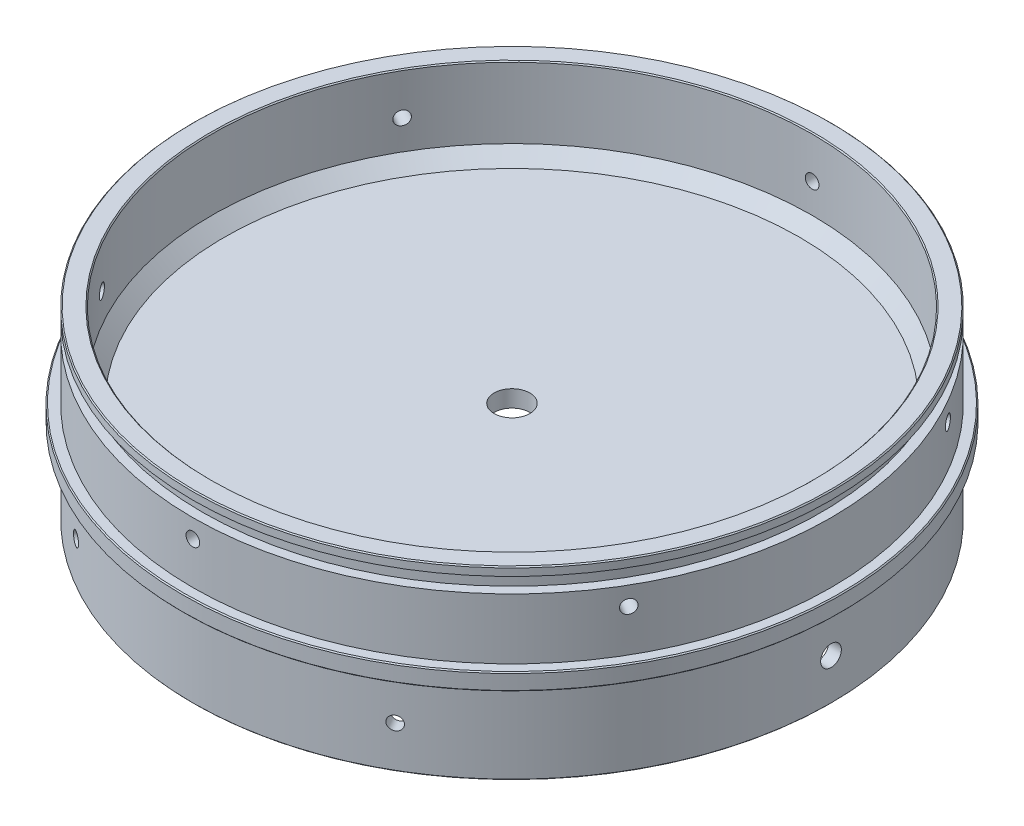
SolidWorks part; units mm, degrees
material "7075-T6 (SN)"
ref_plane "Front Plane" through (0, 0, 0) normal (0, 0, 1) x (1, 0, 0)
ref_plane "Top Plane" through (0, 0, 0) normal (0, 1, 0) x (1, 0, 0)
ref_plane "Right Plane" through (0, 0, 0) normal (1, 0, 0) x (0, 0, -1)
ref_plane "Plane1" through (0, 0, 0) normal (0, 0, -1) x (-1, 0, 0)
sketch "Sketch1" plane through (0, 0, 0) normal (0, 0, -1) x (-1, 0, 0)
  line L0 (-78.35, 0) -> (0, 0)
  line L1 (0, 0) -> (0, 24)
  line L2 (0, 24) -> (-75.89, 24)
  line L3 (-75.89, 24) -> (-75.89, 22)
  line L4 (-75.89, 22) -> (-73.64, 22)
  line L5 (-73.64, 22) -> (-73.64, 18.4)
  line L6 (-73.64, 18.4) -> (-75.89, 18.4)
  line L7 (-75.89, 18.4) -> (-75.89, 4)
  line L8 (-75.89, 4) -> (-78.35, 4)
  line L9 (-78.35, 4) -> (-78.35, 0)
  line L10 (0, 0) -> (0, 24) construction
revolve "Revolve1" add sketch "Sketch1" angle 360 about L10
sketch "Sketch2" plane through (0, 0, 0) normal (0, -1, 0) x (1, 0, 0)
  circle A0 centre (0, 0) radius 75.89
extrude "Boss-Extrude1" add sketch "Sketch2" along normal blind 20
sketch "Sketch3" plane through (0, 0, 0) normal (0, 0, 1) x (1, 0, 0)
  line L0 (71.39, 24) -> (0, 24)
  line L1 (0, 24) -> (0, -20)
  line L2 (0, -20) -> (72.89, -20)
  line L3 (72.89, -20) -> (72.89, 0)
  line L4 (72.89, 0) -> (4.25, 0)
  line L5 (4.25, 0) -> (4.25, 4)
  line L6 (4.25, 4) -> (71.39, 4)
  line L7 (71.39, 4) -> (71.39, 24)
  line L8 (0, 24) -> (0, -20) construction
revolve "Cut-Revolve1" cut sketch "Sketch3" angle 360 about L8
hole_wizard "M3 Clearance Hole1" positions "3DSketch1" profile "Sketch4" hole size "M3" standard "ANSI Metric"
sketch3d "3DSketch1"
  point P0 (65.7227, 14, -37.945)
sketch "Sketch4" plane through (65.7227, 14, -37.945) normal (0, 1, 0) x (-0.5, 0, -0.866)
  line L0 (0, 0) -> (0, 156.2984)
  line L1 (0, 156.2984) -> (1.62, 156.2984)
  line L2 (1.62, 156.2984) -> (1.62, 0)
  line L5 (1.62, 0) -> (0, 0)
  line L10 (0, 156.2984) -> (-1.62, 156.2984) construction
  line L11 (0, -6.35) -> (0, 107.95) construction
  dimension "Hole Dia." = 3.24
  dimension "Hole Depth" = 156.2984
  dimension "Drill Angle" = 180
hole_wizard "M3 Clearance Hole2" positions "3DSketch2" profile "Sketch5" hole size "M3" standard "ANSI Metric"
sketch3d "3DSketch2"
  point P0 (65.7227, 14, 37.945)
sketch "Sketch5" plane through (65.7227, 14, 37.945) normal (0, 1, 0) x (0.5, 0, -0.866)
  line L0 (0, 0) -> (0, 156.2984)
  line L1 (0, 156.2984) -> (1.62, 156.2984)
  line L2 (1.62, 156.2984) -> (1.62, 0)
  line L5 (1.62, 0) -> (0, 0)
  line L10 (0, 156.2984) -> (-1.62, 156.2984) construction
  line L11 (0, -6.35) -> (0, 107.95) construction
  dimension "Hole Dia." = 3.24
  dimension "Hole Depth" = 156.2984
  dimension "Drill Angle" = 180
hole_wizard "M3 Clearance Hole3" positions "3DSketch3" profile "Sketch6" hole size "M3" standard "ANSI Metric"
sketch3d "3DSketch3"
  point P0 (0, 14, 75.89)
sketch "Sketch6" plane through (0, 14, 75.89) normal (1, 0, 0) x (0, -1, 0)
  line L0 (0, 0) -> (0, 156.2984)
  line L1 (0, 156.2984) -> (1.62, 156.2984)
  line L2 (1.62, 156.2984) -> (1.62, 0)
  line L5 (1.62, 0) -> (0, 0)
  line L10 (0, 156.2984) -> (-1.62, 156.2984) construction
  line L11 (0, -6.35) -> (0, 107.95) construction
  dimension "Hole Dia." = 3.24
  dimension "Hole Depth" = 156.2984
  dimension "Drill Angle" = 180
hole_wizard "Hole1" positions "3DSketch4" profile "Sketch7" legacy
sketch3d "3DSketch4"
  point P0 (75.89, -10, 0)
sketch "Sketch7" plane through (75.89, -10, 0) normal (0, 1, 0) x (0, 0, -1)
  line L0 (0, 0) -> (0, 3)
  line L1 (0, 3) -> (2.46, 3)
  line L2 (2.46, 3) -> (2.46, 0)
  line L3 (2.46, 0) -> (0, 0)
  line L4 (0, 110) -> (0, -10) construction
  dimension "Diameter" = 4.92
  dimension "Depth" = 3
hole_wizard "M3 Clearance Hole4" positions "3DSketch5" profile "Sketch8" hole size "M3" standard "ANSI Metric"
sketch3d "3DSketch5"
  point P0 (-75.89, -10, 0)
sketch "Sketch8" plane through (-75.89, -10, 0) normal (0, 1, 0) x (0, 0, 1)
  line L0 (0, 0) -> (0, 154.24)
  line L1 (0, 154.24) -> (1.62, 154.24)
  line L2 (1.62, 154.24) -> (1.62, 0)
  line L5 (1.62, 0) -> (0, 0)
  line L11 (0, -6.35) -> (0, 107.95) construction
  dimension "Thru Hole Dia." = 3.24
  dimension "Thru Hole Depth" = 154.24
hole_wizard "M3 Clearance Hole5" positions "3DSketch6" profile "Sketch9" hole size "M3" standard "ANSI Metric"
sketch3d "3DSketch6"
  point P0 (37.945, -10, -65.7227)
sketch "Sketch9" plane through (37.945, -10, -65.7227) normal (0, 1, 0) x (-0.866, 0, -0.5)
  line L0 (0, 0) -> (0, 154.798)
  line L1 (0, 154.798) -> (1.62, 154.798)
  line L2 (1.62, 154.798) -> (1.62, 0)
  line L5 (1.62, 0) -> (0, 0)
  line L10 (0, 154.798) -> (-1.62, 154.798) construction
  line L11 (0, -6.35) -> (0, 107.95) construction
  dimension "Hole Dia." = 3.24
  dimension "Hole Depth" = 154.798
  dimension "Drill Angle" = 180
hole_wizard "M3 Clearance Hole6" positions "3DSketch7" profile "Sketch10" hole size "M3" standard "ANSI Metric"
sketch3d "3DSketch7"
  point P0 (37.945, -10, 65.7227)
sketch "Sketch10" plane through (37.945, -10, 65.7227) normal (0, 1, 0) x (0.866, 0, -0.5)
  line L0 (0, 0) -> (0, 154.798)
  line L1 (0, 154.798) -> (1.62, 154.798)
  line L2 (1.62, 154.798) -> (1.62, 0)
  line L5 (1.62, 0) -> (0, 0)
  line L10 (0, 154.798) -> (-1.62, 154.798) construction
  line L11 (0, -6.35) -> (0, 107.95) construction
  dimension "Hole Dia." = 3.24
  dimension "Hole Depth" = 154.798
  dimension "Drill Angle" = 180
chamfer "Chamfer1" distance 0.25 angle 45 6 edges at (0, 24, 75.89) (0, -20, -72.89) (0, 4, 78.35) (0, 24, -71.39) (0, 0, 78.35) (0, -20, -75.89)
chamfer "Chamfer2" distance 3 angle 45 2 edges at (0, 4, -71.39) (0, 0, -72.89)
